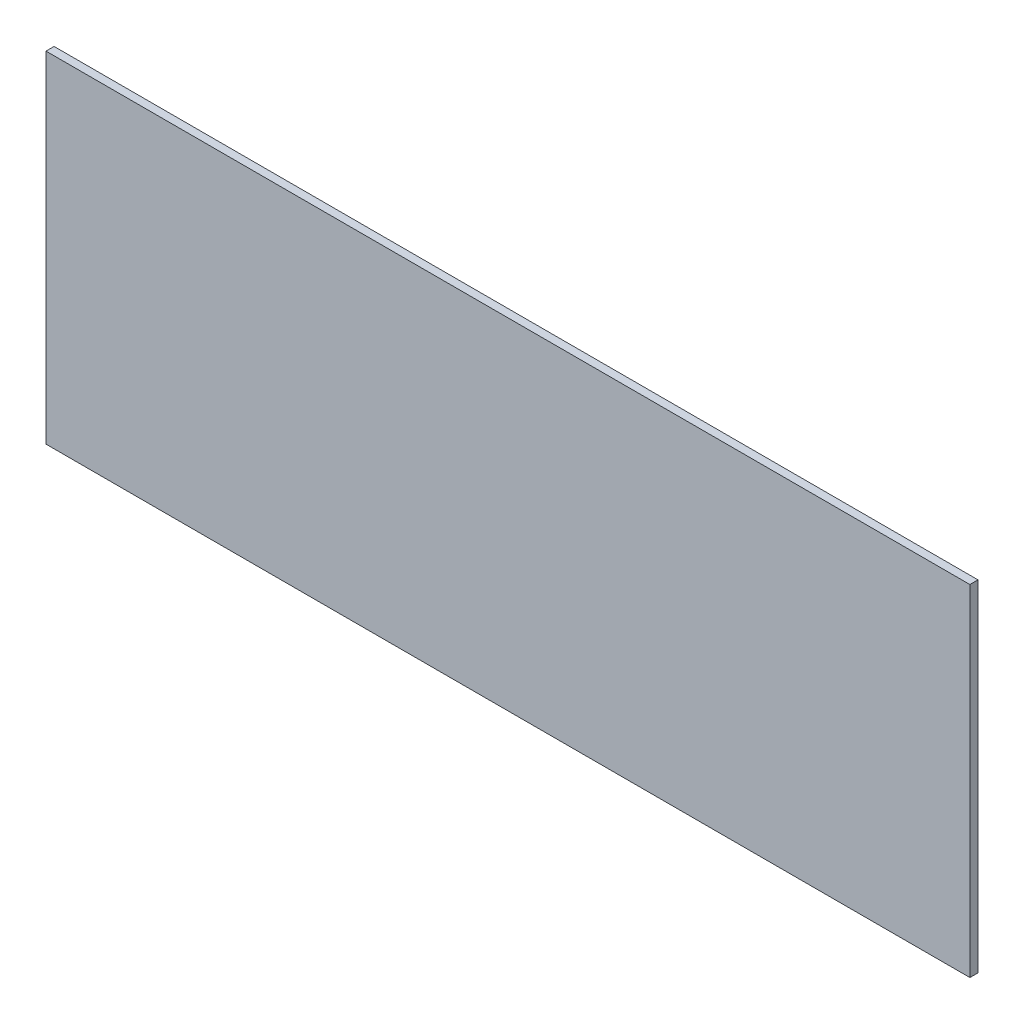
SolidWorks part; units mm, degrees
ref_plane "Plan de face" through (0, 0, 0) normal (0, 0, 1) x (1, 0, 0)
ref_plane "Plan de dessus" through (0, 0, 0) normal (0, 1, 0) x (1, 0, 0)
ref_plane "Plan de droite" through (0, 0, 0) normal (1, 0, 0) x (0, 0, -1)
sketch "Esquisse1" plane through (0, 0, 0) normal (0, 0, 1) x (1, 0, 0)
  line L1 (-180.975, 66.675) -> (180.975, 66.675)
  line L2 (-180.975, 66.675) -> (-180.975, -66.675)
  line L3 (-180.975, -66.675) -> (180.975, -66.675)
  line L4 (180.975, 66.675) -> (180.975, -66.675)
  point P4 (0, -66.675)
  point P6 (-180.975, 0)
  dimension "D1" = 361.95
  dimension "D2" = 133.35
extrude "Boss.-Extru.1" add sketch "Esquisse1" along normal mid plane 3.175
